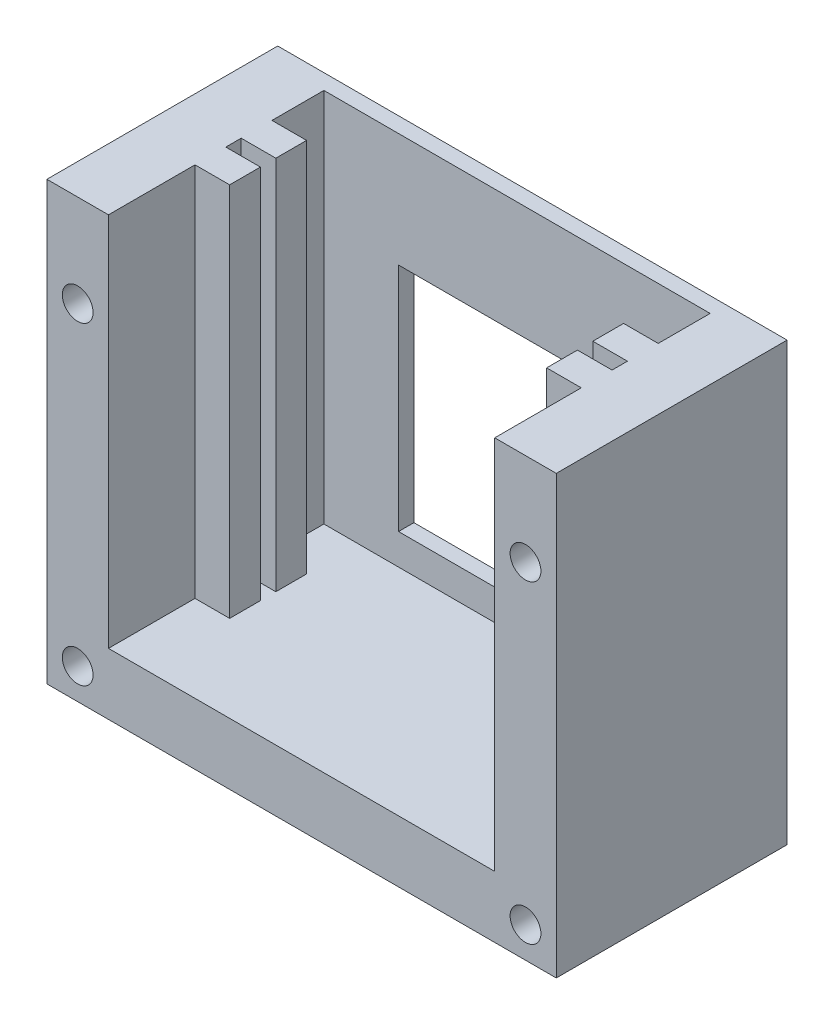
SolidWorks part; units mm, degrees
ref_plane "Plan de face" through (0, 0, 0) normal (0, 0, 1) x (1, 0, 0)
ref_plane "Plan de dessus" through (0, 0, 0) normal (0, 1, 0) x (1, 0, 0)
ref_plane "Plan de droite" through (0, 0, 0) normal (1, 0, 0) x (0, 0, -1)
sketch "Esquisse1" plane through (0, 0, 0) normal (0, 0, 1) x (1, 0, 0)
  line L0 (0, 0) -> (0, -27) construction
  line L1 (0, -27) -> (0, 30) construction
  line L2 (0, 0) -> (25.4165, -15.9375) construction
  line L3 (25.4165, -15.9375) -> (-22.8748, 14.3437) construction
  line L4 (-25.4165, -15.9375) -> (0, 0) construction
  line L5 (0, 0) -> (22.8748, 14.3437) construction
  line L6 (0, 30) -> (25.4165, -15.9375) construction
  line L8 (12.5, -14) -> (-12.5, -14)
  line L9 (12.5, -14) -> (12.5, -17)
  line L10 (12.5, -17) -> (-12.5, -17)
  line L11 (-12.5, -14) -> (-12.5, -17)
  circle A0 centre (0, 0) radius 37
  circle A1 centre (0, 30) radius 1.5
  circle A2 centre (-22.8748, 14.3437) radius 1.5
  circle A3 centre (-25.4165, -15.9375) radius 1.5
  circle A4 centre (0, -27) radius 1.5
  circle A5 centre (25.4165, -15.9375) radius 1.5
  circle A6 centre (22.8748, 14.3437) radius 1.5
  dimension "D1" = 74
  dimension "D11" = 3
  dimension "D12" = 3
  dimension "D13" = 3
  dimension "D14" = 3
  dimension "D15" = 3
  dimension "D16" = 3
  dimension "D2" = 27
  dimension "D3" = 57
  dimension "D4" = 57
  dimension "D5" = 30
  dimension "D6" = 30
  dimension "D7" = 27
  dimension "D8" = 52.5
  dimension "D9" = 52.5
  dimension "D10" = 47.25
  dimension "D17" = 25
  dimension "D18" = 3
  dimension "D19" = 10
  dimension "D20" = 12.5
extrude "Boss.-Extru.1" add sketch "Esquisse1" along normal blind 2
sketch "Esquisse2" plane through (0, 0, 0) normal (0, 0, -1) x (-1, 0, 0)
  line L0 (-16.75, 14.9) -> (-16.75, -13.5)
  line L1 (-12.75, 14.9) -> (12.35, 14.9)
  line L2 (-12.75, 14.9) -> (-12.75, -9.5)
  line L3 (-12.75, -9.5) -> (12.35, -9.5)
  line L4 (12.35, 14.9) -> (12.35, -9.5)
  line L5 (-16.75, -13.5) -> (16.35, -13.5)
  line L6 (16.35, -13.5) -> (16.35, 14.9)
  line L7 (16.35, 14.9) -> (12.35, 14.9)
  line L8 (-16.75, 14.9) -> (-12.75, 14.9)
  point P0 (0, 0)
  dimension "D1" = 25.1
  dimension "D2" = 9.5
  dimension "D3" = 24.4
  dimension "D4" = 4
  dimension "D5" = 4
  dimension "D6" = 4
  dimension "D7" = 12.75
extrude "Boss.-Extru.2" add sketch "Esquisse2" along normal blind 15 contours L8 L0 L5 L6 L7 L4 L3 L2
sketch "Esquisse3" plane through (-12.35, 0, 0) normal (1, 0, 0) x (0, 0, -1)
  line L0 (15, 14.9) -> (0, 14.9) construction
  line L1 (10.625, 14.9) -> (8.625, 14.9)
  line L2 (10.625, 14.9) -> (10.625, -13.5)
  line L3 (10.625, -13.5) -> (8.625, -13.5)
  line L4 (8.625, 14.9) -> (8.625, -13.5)
  line L5 (15, -13.5) -> (0, -13.5) construction
  line L6 (0, 14.9) -> (7.5, 14.9) construction
  line L8 (5.625, 14.9) -> (7.625, 14.9)
  line L9 (5.625, 14.9) -> (5.625, -13.5)
  line L10 (5.625, -13.5) -> (7.625, -13.5)
  line L11 (7.625, 14.9) -> (7.625, -13.5)
  line L12 (8, 14.9) -> (8, -13.5) construction
  point P17 (0, 0)
  point P18 (0, 0)
  point P19 (0, 0)
  point P20 (0, 0)
  point P21 (0, 0)
  point P22 (0, 0)
  dimension "D1" = 2
  dimension "D2" = 0.625
  dimension "D3" = 2
  dimension "D4" = 1
  dimension "D5" = 0.375
  dimension "D6" = 0.5
extrude "Boss.-Extru.3" add sketch "Esquisse3" along normal blind 2.25 contours L11 L10 L9 L8 | L2 L3 L4 L1
sketch "Esquisse5" plane through (12.75, 0, 0) normal (-1, 0, 0) x (0, 0, 1)
  line L1 (-10.625, 14.9) -> (-8.625, 14.9)
  line L2 (-10.625, 14.9) -> (-10.625, -9.5)
  line L3 (-10.625, -9.5) -> (-8.625, -9.5)
  line L4 (-8.625, 14.9) -> (-8.625, -9.5)
  line L5 (-7.625, 14.9) -> (-5.625, 14.9)
  line L6 (-7.625, 14.9) -> (-7.625, -9.5)
  line L7 (-7.625, -9.5) -> (-5.625, -9.5)
  line L8 (-5.625, 14.9) -> (-5.625, -9.5)
extrude "Boss.-Extru.4" add sketch "Esquisse5" along normal blind 2.25
sketch "Esquisse7" plane through (0, 0, -15) normal (0, 0, -1) x (-1, 0, 0)
  line L1 (-16.75, 14.9) -> (16.35, 14.9)
  line L2 (-16.75, 14.9) -> (-16.75, -13.5)
  line L3 (-16.75, -13.5) -> (16.35, -13.5)
  line L4 (16.35, 14.9) -> (16.35, -13.5)
extrude "Boss.-Extru.5" add sketch "Esquisse7" against normal blind 1
sketch "Esquisse8" plane through (0, 0, -15) normal (0, 0, -1) x (-1, 0, 0)
  line L1 (-7.5, 7.5) -> (7.5, 7.5)
  line L2 (-7.5, 7.5) -> (-7.5, -7.5)
  line L3 (-7.5, -7.5) -> (7.5, -7.5)
  line L4 (7.5, 7.5) -> (7.5, -7.5)
  line L5 (-7.5, 7.5) -> (7.5, -7.5) construction
  line L6 (-7.5, -7.5) -> (7.5, 7.5) construction
  point P0 (0, 0)
  dimension "D1" = 15
  dimension "D2" = 15
extrude "Enlèv. mat.-Extru.1" cut sketch "Esquisse8" against normal blind 3 contours L3 L4 L1 L2
sketch "Esquisse9" plane through (0, -13.5, 0) normal (0, -1, 0) x (1, 0, 0)
  line L0 (16.75, 0) -> (-16.35, 0) construction
  line L1 (-10.5, -4.4) -> (10.5, -4.4)
  line L2 (-10.5, -4.4) -> (-10.5, -6.9)
  line L3 (-10.5, -6.9) -> (10.5, -6.9)
  line L4 (10.5, -4.4) -> (10.5, -6.9)
  line L6 (10.5, -4.4) -> (10.5, 0) construction
  line L7 (10.5, 0) -> (-10.5, 0) construction
  line L8 (-10.5, 0) -> (-10.5, -4.4) construction
  point P6 (0, -4.4)
  dimension "D1" = 21
  dimension "D2" = 2.5
  dimension "D3" = 4.4
  dimension "D4" = 0
extrude "Enlèv. mat.-Extru.2" cut sketch "Esquisse9" against normal blind 3 contours L1 L4 L3 L2
sketch "Esquisse10" plane through (0, 0, 2) normal (0, 0, 1) x (1, 0, 0)
  line L0 (16.75, -13.5) -> (-16.35, -13.5) construction
  line L1 (-16.35, -13.5) -> (-16.35, 14.9) construction
  line L2 (16.75, 14.9) -> (16.75, -13.5) construction
  line L3 (16.75, 14.9) -> (12.75, 14.9) construction
  line L4 (-16.35, 14.9) -> (-12.35, 14.9) construction
  circle A0 centre (-14.35, 8.9) radius 1
  circle A1 centre (-14.35, -11.5) radius 1
  circle A2 centre (14.75, -11.5) radius 1
  circle A3 centre (14.75, 8.9) radius 1
  dimension "D1" = 2
  dimension "D2" = 2
  dimension "D3" = 2
  dimension "D4" = 2
  dimension "D5" = 2
  dimension "D6" = 2
  dimension "D7" = 2
  dimension "D8" = 2
  dimension "D9" = 2
  dimension "D10" = 6
  dimension "D11" = 6
  dimension "D12" = 2
extrude "Enlèv. mat.-Extru.3" cut sketch "Esquisse10" against normal blind 19
sketch "Esquisse11" plane through (0, 0, 2) normal (0, 0, 1) x (1, 0, 0)
  circle A0 centre (0, 0) radius 37
extrude "Enlèv. mat.-Extru.4" cut sketch "Esquisse11" against normal blind 2
